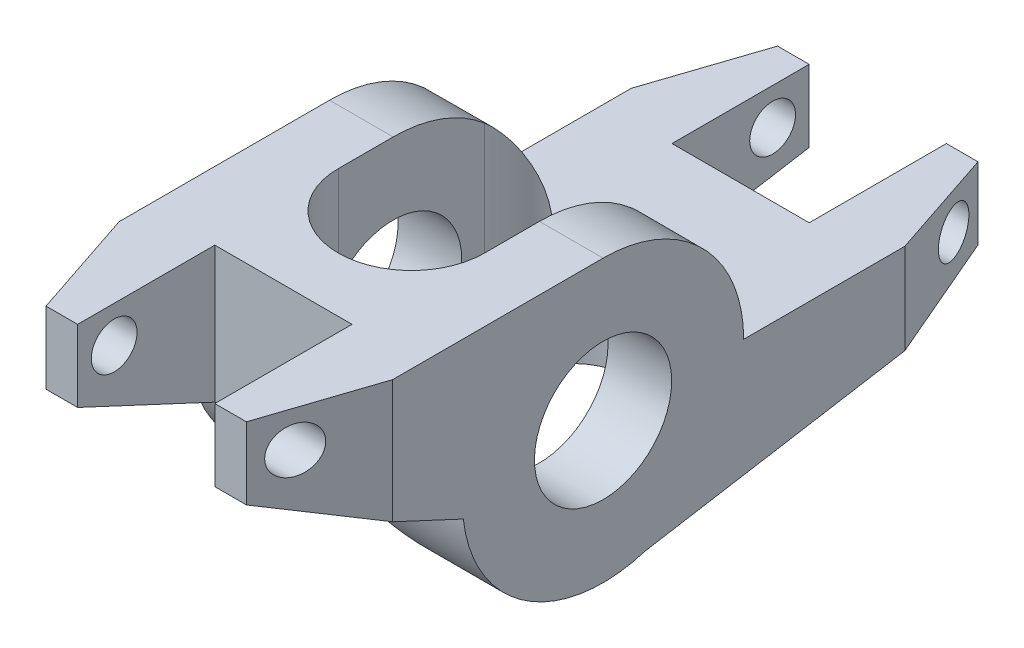
SolidWorks part; units mm, degrees
ref_plane "Front Plane" through (0, 0, 0) normal (0, 0, 1) x (1, 0, 0)
ref_plane "Top Plane" through (0, 0, 0) normal (0, 1, 0) x (1, 0, 0)
ref_plane "Right Plane" through (0, 0, 0) normal (1, 0, 0) x (0, 0, -1)
sketch "Sketch1" plane through (0, 0, 0) normal (1, 0, 0) x (0, 0, -1)
  line L0 (0, 9.765) -> (-22.23, 9.765)
  line L1 (-22.23, 9.765) -> (-22.23, 4.765)
  line L2 (-22.23, 4.765) -> (-9.7056, -1.0752)
  line L3 (9.765, 0) -> (28.58, 0)
  line L4 (28.58, 0) -> (28.58, -5)
  line L5 (28.58, -5) -> (2.9417, -9.3114)
  circle A0 centre (0, 0) radius 4.765
  arc A1 (-9.7056, -1.0752) -> (2.9417, -9.3114) centre (0, 0) ccw
  arc A2 (9.765, 0) -> (0, 9.765) centre (0, 0) ccw
  circle A3 centre (0, 0) radius 9.765 construction
  point P11 (1.1084, -9.7019)
  point P14 (2.9417, -9.3114)
  point P15 (9.765, 0)
  dimension "D1" = 9.53
  dimension "D3" = 22.23
  dimension "D4" = 5
  dimension "D5" = 25
  dimension "D6" = 28.58
  dimension "D7" = 5
  dimension "D2" = 5
extrude "Boss-Extrude1" add sketch "Sketch1" along normal mid plane 19
chamfer "Chamfer1" distance 2.54 distance2 7.62 2 edges at (9.5, -2.5, -28.58) (9.5, 7.265, 22.23)
chamfer "Chamfer2" distance 7.62 distance2 2.54 2 edges at (-9.5, -2.5, -28.58) (-9.5, 7.265, 22.23)
sketch "Sketch2" plane through (0, 0, 0) normal (0, 1, 0) x (1, 0, 0)
  line L0 (0, -3.81) -> (0, 6.35) construction
  line L1 (-5.08, -3.81) -> (-5.08, 6.35)
  line L2 (5.08, -3.81) -> (5.08, 6.35)
  arc A0 (-5.08, -3.81) -> (5.08, -3.81) centre (0, -3.81) ccw
  arc A1 (5.08, 6.35) -> (-5.08, 6.35) centre (0, 6.35) ccw
  point P3 (0, 1.27)
  point P8 (0, 0)
  dimension "D1" = 10.16
  dimension "D2" = 10.16
  dimension "D3" = 3.81
extrude "Cut-Extrude1" cut sketch "Sketch2" against normal through all both and the other way through all
sketch "Sketch3" plane through (0, 0, 0) normal (0, 1, 0) x (1, 0, 0)
  line L0 (6.96, 28.58) -> (-6.96, 28.58) construction
  line L1 (4.765, 19.05) -> (-4.765, 19.05)
  line L2 (4.765, 19.05) -> (4.765, 28.58)
  line L3 (4.765, 28.58) -> (-4.765, 28.58)
  line L4 (-4.765, 19.05) -> (-4.765, 28.58)
  line L5 (4.765, 19.05) -> (-4.765, 28.58) construction
  line L6 (4.765, 28.58) -> (-4.765, 19.05) construction
  line L7 (6.96, -22.23) -> (-6.96, -22.23) construction
  line L8 (-4.765, -12.7) -> (4.765, -12.7)
  line L9 (-4.765, -12.7) -> (-4.765, -22.23)
  line L10 (-4.765, -22.23) -> (4.765, -22.23)
  line L11 (4.765, -12.7) -> (4.765, -22.23)
  line L12 (-4.765, -12.7) -> (4.765, -22.23) construction
  line L13 (-4.765, -22.23) -> (4.765, -12.7) construction
  point P0 (0, 23.815)
  point P7 (0, -17.465)
  point P14 (0, 0)
  dimension "D1" = 9.53
  dimension "D2" = 9.53
  dimension "D3" = 9.53
  dimension "D4" = 9.53
extrude "Cut-Extrude2" cut sketch "Sketch3" against normal through all both and the other way through all
sketch "Sketch4" plane through (0, 0, 0) normal (1, 0, 0) x (0, 0, -1)
  line L0 (28.58, 0) -> (28.58, -5) construction
  line L2 (20.96, 0) -> (28.58, 0) construction
  line L3 (-22.23, 9.765) -> (-14.61, 9.765) construction
  line L4 (-22.23, 4.765) -> (-22.23, 9.765) construction
  circle A0 centre (-19.69, 7.225) radius 1.59
  circle A1 centre (26.04, -2.54) radius 1.59
  point P9 (23.6874, 0)
  point P12 (-39.3111, 8.5243)
  point P13 (-40.8265, 21.5678)
  dimension "D1" = 3.18
  dimension "D4" = 3.18
  dimension "D2" = 2.54
  dimension "D3" = 2.54
  dimension "D5" = 2.54
  dimension "D6" = 2.54
extrude "Cut-Extrude3" cut sketch "Sketch4" against normal through all both and the other way through all
